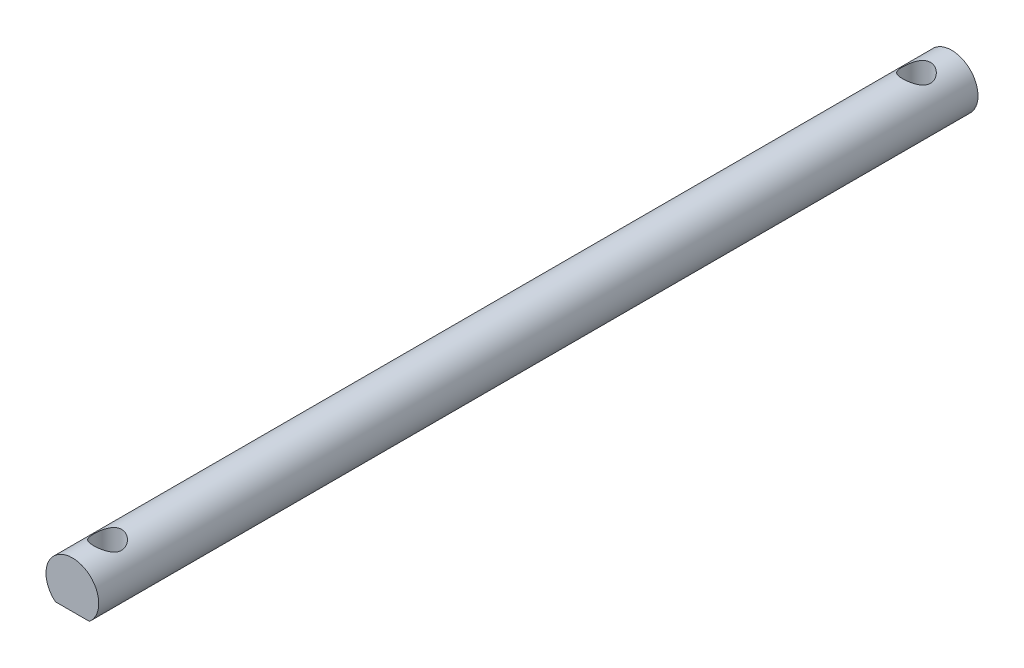
SolidWorks part; units mm, degrees
ref_plane "Front Plane" through (0, 0, 0) normal (0, 0, 1) x (1, 0, 0)
ref_plane "Top Plane" through (0, 0, 0) normal (0, 1, 0) x (1, 0, 0)
ref_plane "Right Plane" through (0, 0, 0) normal (1, 0, 0) x (0, 0, -1)
sketch "Sketch1" plane through (0, 0, 0) normal (0, 0, 1) x (1, 0, 0)
  circle A0 centre (0, 3.1473) radius 1.5
  dimension "D1" = 3
extrude "Boss-Extrude1" add sketch "Sketch1" along normal blind 50
sketch "Sketch3" plane through (0, 0, 0) normal (0, 1, 0) x (1, 0, 0)
  line L0 (1.5, -50) -> (1.5, 0) construction
  line L1 (-1, -46.5) -> (1, -46.5)
  line L2 (-1, -46.5) -> (-1, -51)
  line L3 (-1, -51) -> (1, -51)
  line L4 (1, -46.5) -> (1, -51)
  line L5 (-1.5, 0) -> (-1.5, -50) construction
  line L6 (-1.5, -50) -> (1.5, -50) construction
  line L7 (-1, 1) -> (1, 1)
  line L8 (-1, 1) -> (-1, -3.5)
  line L9 (-1, -3.5) -> (1, -3.5)
  line L10 (1, 1) -> (1, -3.5)
  line L11 (1.5, 0) -> (-1.5, 0) construction
  dimension "D1" = 2
  dimension "D2" = 0.5
  dimension "D3" = 0.5
  dimension "D4" = 3.5
  dimension "D5" = 1
  dimension "D6" = 2
  dimension "D7" = 0.5
  dimension "D8" = 0.5
  dimension "D9" = 3.5
  dimension "D10" = 1
extrude "Cut-Extrude1" cut sketch "Sketch3" against normal blind 50 and the other way blind 2
sketch "Sketch4" plane through (0, 0, 0) normal (0, 1, 0) x (1, 0, 0)
  line L0 (-1.5, 0) -> (-1.5, -50) construction
  line L1 (-1.5, -50) -> (1.5, -50) construction
  line L2 (0.9663, 0) -> (-0.9663, 0) construction
  line L3 (1.5, -50) -> (1.5, 0) construction
  circle A0 centre (0, -48) radius 0.8
  circle A1 centre (0, -2) radius 0.8
  dimension "D1" = 1.6
  dimension "D4" = 1.6
  dimension "D2" = 1.5
  dimension "D3" = 2
  dimension "D5" = 2
  dimension "D6" = 1.5
extrude "Cut-Extrude2" cut sketch "Sketch4" against normal blind 50 and the other way blind 50
